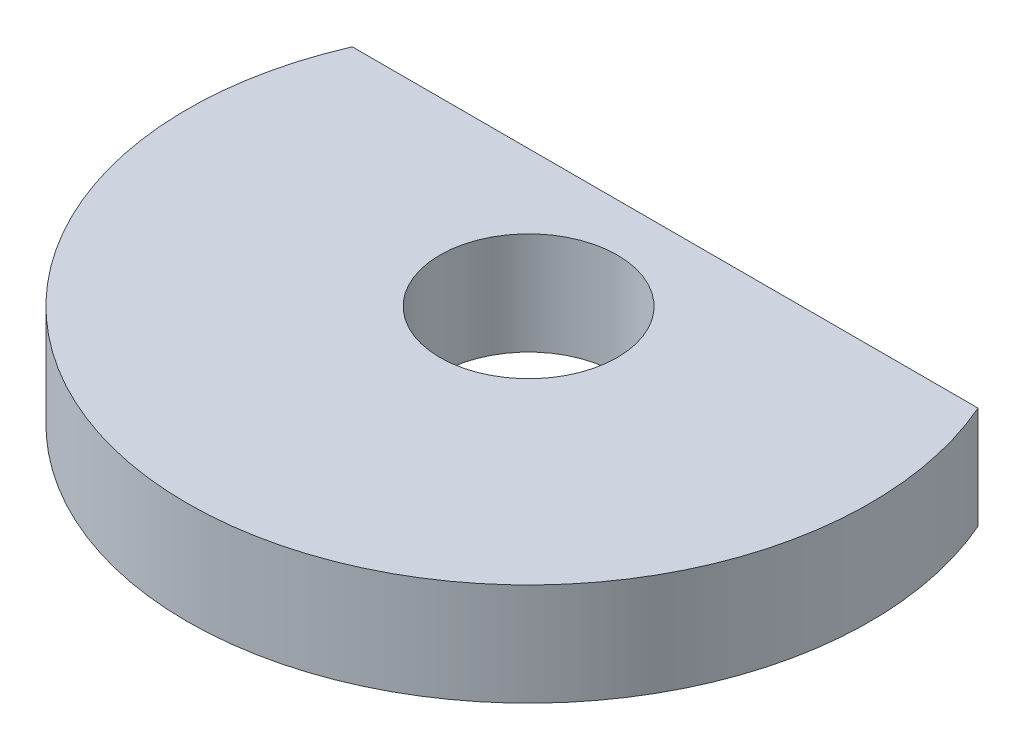
SolidWorks part; units mm, degrees
ref_plane "前视基准面" through (0, 0, 0) normal (0, 0, 1) x (1, 0, 0)
ref_plane "上视基准面" through (0, 0, 0) normal (0, 1, 0) x (1, 0, 0)
ref_plane "右视基准面" through (0, 0, 0) normal (1, 0, 0) x (0, 0, -1)
sketch "草图1" plane through (0, 0, 0) normal (0, 1, 0) x (1, 0, 0)
  line L0 (-9.1652, 4) -> (9.1652, 4)
  circle A0 centre (0, 0) radius 10
  circle A1 centre (0, 0) radius 2.6
  dimension "D1" = 20
  dimension "D2" = 5.2
  dimension "D3" = 4
extrude "凸台-拉伸1" add sketch "草图1" along normal blind 3 contours L0 A0 A1
